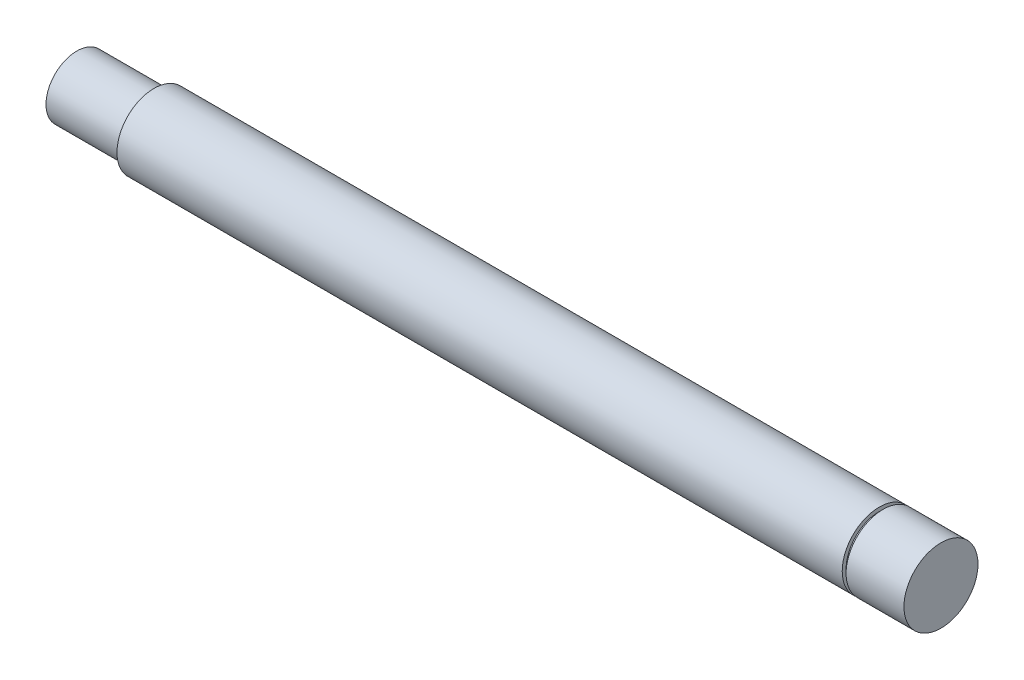
SolidWorks part; units mm, degrees
material "PW20:29:Sc:0:"
ref_plane "Front" through (0, 0, 0) normal (0, 0, 1) x (1, 0, 0)
ref_plane "Top" through (0, 0, 0) normal (0, 1, 0) x (1, 0, 0)
ref_plane "Right" through (0, 0, 0) normal (1, 0, 0) x (0, 0, -1)
sketch "Sketch1" plane through (0, 0, 0) normal (1, 0, 0) x (0, 0, -1)
  circle A0 centre (0, 0) radius 7.62
  dimension "D1" = 15.24
extrude "Base-Extrude" add sketch "Sketch1" along normal blind 177.8
ref_plane "Plane4" through (165.8937, 0, 0) normal (1, 0, 0) x (0, 0, -1)
sketch "Sketch2" plane through (165.8937, 0, 0) normal (1, 0, 0) x (0, 0, -1)
  circle A1 centre (0, 0) radius 6.8262
  circle A2 centre (0, 0) radius 6.8262
  circle A3 centre (0, 0) radius 7.62
  circle A4 centre (0, 0) radius 7.62
  dimension "D1" = 0.7937
  dimension "D2" = 0
extrude "Cut-Extrude1" cut sketch "Sketch2" against normal blind 0.7937
sketch "Sketch3" plane through (0, 0, 0) normal (-1, 0, 0) x (0, 0, 1)
  circle A0 centre (0, 0) radius 7.62 construction
  circle A1 centre (0, 0) radius 6.35
  circle A2 centre (0, 0) radius 6.35
  circle A3 centre (0, 0) radius 7.62
  dimension "D1" = 1.27
extrude "Cut-Extrude2" cut sketch "Sketch3" against normal blind 15.875
sketch "Sketch4" [suppressed] plane through (177.8, 0, 0) normal (1, 0, 0) x (0, 0, -1)
  circle A0 centre (0, 0) radius 4.7625
  dimension "D1" = 9.525
extrude "Cut-Extrude3" [suppressed] cut sketch "Sketch4" against normal blind 25.4
